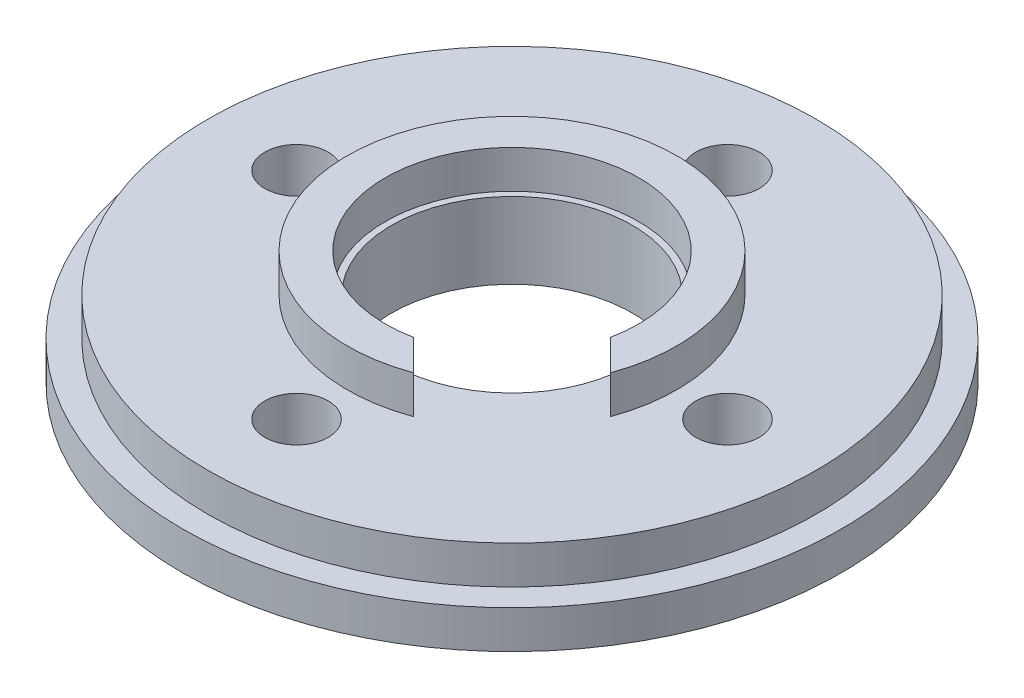
SolidWorks part; units mm, degrees
ref_plane "Front Plane" through (0, 0, 0) normal (0, 0, 1) x (1, 0, 0)
ref_plane "Top Plane" through (0, 0, 0) normal (0, 1, 0) x (1, 0, 0)
ref_plane "Right Plane" through (0, 0, 0) normal (1, 0, 0) x (0, 0, -1)
sketch "Sketch1" plane through (0, 0, 0) normal (0, 1, 0) x (1, 0, 0)
  circle A0 centre (0, 0) radius 13
extrude "Boss-Extrude1" add sketch "Sketch1" along normal blind 1.5
sketch "Sketch2" plane through (0, 1.5, 0) normal (0, 1, 0) x (1, 0, 0)
  circle A0 centre (0, 0) radius 12
extrude "Boss-Extrude2" add sketch "Sketch2" along normal blind 1.5
sketch "Sketch3" plane through (0, 3, 0) normal (0, 1, 0) x (1, 0, 0)
  circle A0 centre (0, 0) radius 6.5
extrude "Boss-Extrude3" add sketch "Sketch3" along normal blind 1.5
sketch "Sketch4" plane through (0, 3, 0) normal (0, 1, 0) x (1, 0, 0)
  circle A0 centre (0, 0) radius 8.5 construction
  circle A1 centre (-8.5, 0) radius 1.25
  circle A2 centre (0, 8.5) radius 1.25
  circle A3 centre (8.5, 0) radius 1.25
  circle A4 centre (0, -8.5) radius 1.25
  point P14 (0, 0)
  dimension "D1" = 4
extrude "Cut-Extrude1" cut sketch "Sketch4" against normal blind 11.5
sketch "Sketch5" plane through (0, 4.5, 0) normal (0, 1, 0) x (1, 0, 0)
  circle A0 centre (0, 0) radius 4.75
extrude "Cut-Extrude2" cut sketch "Sketch5" against normal blind 11.5
sketch "Sketch6" plane through (0, 4.5, 0) normal (0, 1, 0) x (1, 0, 0)
  circle A0 centre (0, 0) radius 5
extrude "Cut-Extrude3" cut sketch "Sketch6" against normal blind 1.5
sketch "Sketch7" plane through (0, 4.5, 0) normal (0, 1, 0) x (1, 0, 0)
  line L0 (0.7676, -4.6567) -> (4.6567, -0.7676)
  line L1 (5.4579, -9.347) -> (9.347, -5.4579)
  line L2 (0.7676, -4.6567) -> (5.4579, -9.347)
  line L3 (4.6567, -0.7676) -> (9.347, -5.4579)
extrude "Cut-Extrude4" cut sketch "Sketch7" against normal blind 1.5
